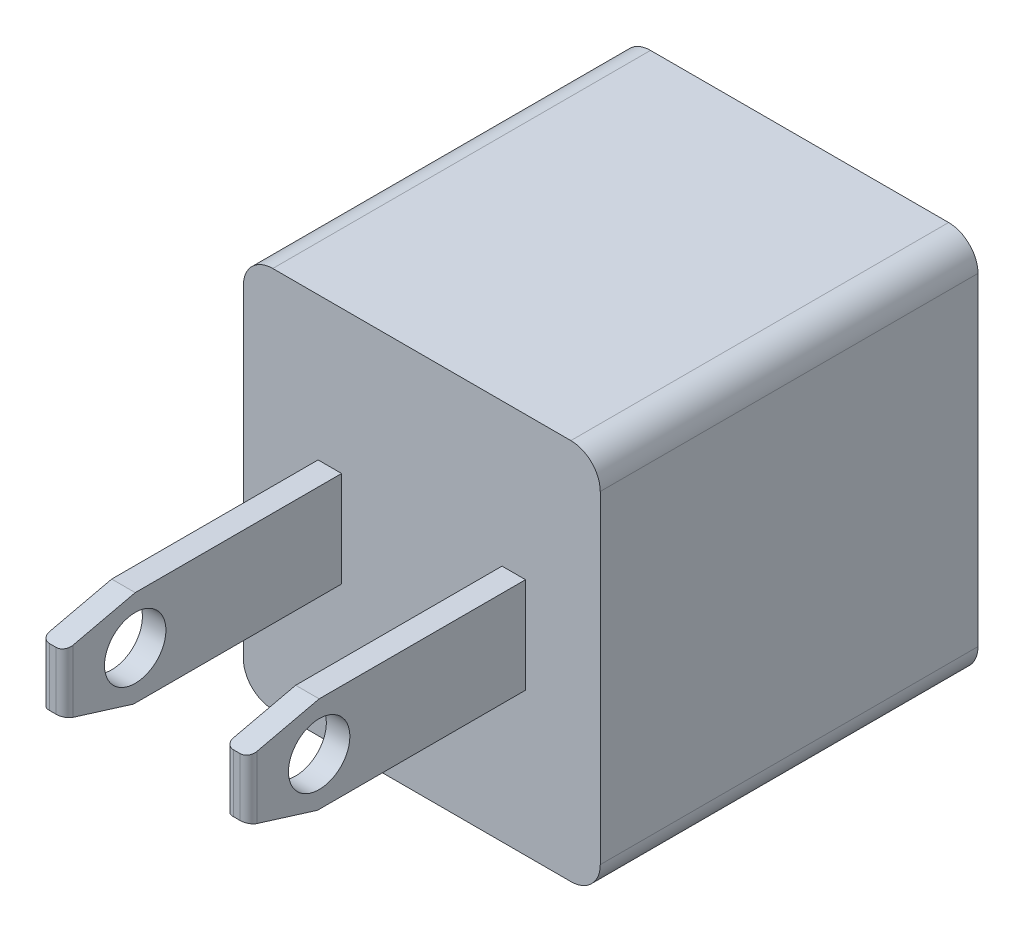
SolidWorks part; units mm, degrees
ref_plane "Front Plane" through (0, 0, 0) normal (0, 0, 1) x (1, 0, 0)
ref_plane "Top Plane" through (0, 0, 0) normal (0, 1, 0) x (1, 0, 0)
ref_plane "Right Plane" through (0, 0, 0) normal (1, 0, 0) x (0, 0, -1)
sketch "Sketch1" plane through (0, 0, 0) normal (0, 0, 1) x (1, 0, 0)
  line L0 (45.102, 57.785) -> (-45.102, 57.785)
  line L1 (-53.992, 48.895) -> (-53.992, -48.895)
  line L2 (-45.102, -57.785) -> (45.102, -57.785)
  line L3 (53.992, -48.895) -> (53.992, 48.895)
  arc A0 (-45.102, 57.785) -> (-53.992, 48.895) centre (-45.102, 48.895) ccw
  arc A1 (53.992, 48.895) -> (45.102, 57.785) centre (45.102, 48.895) ccw
  arc A2 (45.102, -57.785) -> (53.992, -48.895) centre (45.102, -48.895) ccw
  arc A3 (-53.992, -48.895) -> (-45.102, -57.785) centre (-45.102, -48.895) ccw
  point P3 (-53.992, 0)
  point P4 (0, 57.785)
  dimension "D1" = 8.89
  dimension "D2" = 97.79
extrude "Boss-Extrude1" add sketch "Sketch1" along normal blind 114.3
sketch "Sketch2" plane through (0, 0, 0) normal (0, 0, -1) x (-1, 0, 0)
  line L0 (45.102, -57.785) -> (-45.102, -57.785) construction
  line L1 (27.94, -22.225) -> (-27.94, -22.225)
  line L2 (27.94, -22.225) -> (27.94, -42.545)
  line L3 (27.94, -42.545) -> (-27.94, -42.545)
  line L4 (-27.94, -22.225) -> (-27.94, -42.545)
  point P4 (0, -22.225)
  dimension "D1" = 15.24
  dimension "D2" = 55.88
  dimension "D3" = 20.32
extrude "Cut-Extrude1" cut sketch "Sketch2" against normal blind 58.42
sketch "Sketch4" plane through (0, 0, 114.3) normal (0, 0, 1) x (1, 0, 0)
  line L0 (-53.992, 48.895) -> (-53.992, -48.895) construction
  line L1 (-31.386, 14.478) -> (-24.274, 14.478)
  line L2 (-31.386, 14.478) -> (-31.386, -14.478)
  line L3 (-31.386, -14.478) -> (-24.274, -14.478)
  line L4 (-24.274, 14.478) -> (-24.274, -14.478)
  line L5 (24.274, -14.478) -> (24.274, 14.478)
  line L6 (24.274, 14.478) -> (31.386, 14.478)
  line L7 (31.386, 14.478) -> (31.386, -14.478)
  line L8 (31.386, -14.478) -> (24.274, -14.478)
  line L9 (53.992, -48.895) -> (53.992, 48.895) construction
  point P4 (-24.274, 0)
  dimension "D1" = 22.606
  dimension "D2" = 28.956
  dimension "D3" = 7.112
  dimension "D4" = 22.606
  dimension "D5" = 7.112
  dimension "D6" = 28.956
extrude "Boss-Extrude2" add sketch "Sketch4" along normal blind 83.82
sketch "Sketch7" plane through (31.386, 0, 0) normal (1, 0, 0) x (0, 0, -1)
  line L4 (-214.9421, -34.2002) -> (-240.1771, 1.1621)
  line L5 (-240.1771, 1.1621) -> (-200.1373, 42.5448)
  line L7 (-166.1321, 16.9341) -> (-214.9421, 5.6447)
  line L8 (-200.1373, 40.5089) -> (-166.1321, 16.9341)
  line L9 (-166.1321, -17.9302) -> (-204.6488, -5.9767)
  line L10 (-214.9421, -34.2002) -> (-166.1321, -17.9302)
  line L11 (-200.1373, 42.5448) -> (-200.1373, 40.5089)
  line L12 (-204.6488, -5.9767) -> (-214.9421, 5.6447)
extrude "Cut-Extrude3" cut sketch "Sketch7" against normal blind 81.026
sketch "Sketch8" plane through (31.386, 0, 0) normal (1, 0, 0) x (0, 0, -1)
  circle A0 centre (-176.751, 0) radius 9.2907
extrude "Cut-Extrude4" cut sketch "Sketch8" against normal blind 81.026
fillet "Fillet1" radius 2.54 4 edges at (24.274, 0.7663, 198.12) (-24.274, 0.7663, 198.12) (-31.386, 0.7663, 198.12) (31.386, 0.7663, 198.12)
sketch "Sketch9" plane through (0, 0, 0) normal (0, 0, -1) x (-1, 0, 0)
  line L0 (-48.8453, 48.895) -> (-48.8453, -48.895)
  line L1 (45.102, 52.6384) -> (-45.102, 52.6384)
  line L2 (48.8453, -48.895) -> (48.8453, 48.895)
  line L3 (45.102, -52.6384) -> (-45.102, -52.6384)
  arc A0 (-45.102, 52.6384) -> (-48.8453, 48.895) centre (-45.102, 48.895) ccw
  arc A1 (48.8453, 48.895) -> (45.102, 52.6384) centre (45.102, 48.895) ccw
  arc A2 (45.102, -52.6384) -> (48.8453, -48.895) centre (45.102, -48.895) ccw
  arc A3 (-48.8453, -48.895) -> (-45.102, -52.6384) centre (-45.102, -48.895) ccw
  dimension "D1" = 3.7434
extrude "Cut-Extrude-Thin1" cut sketch "Sketch9" against normal blind 2.54 thin
